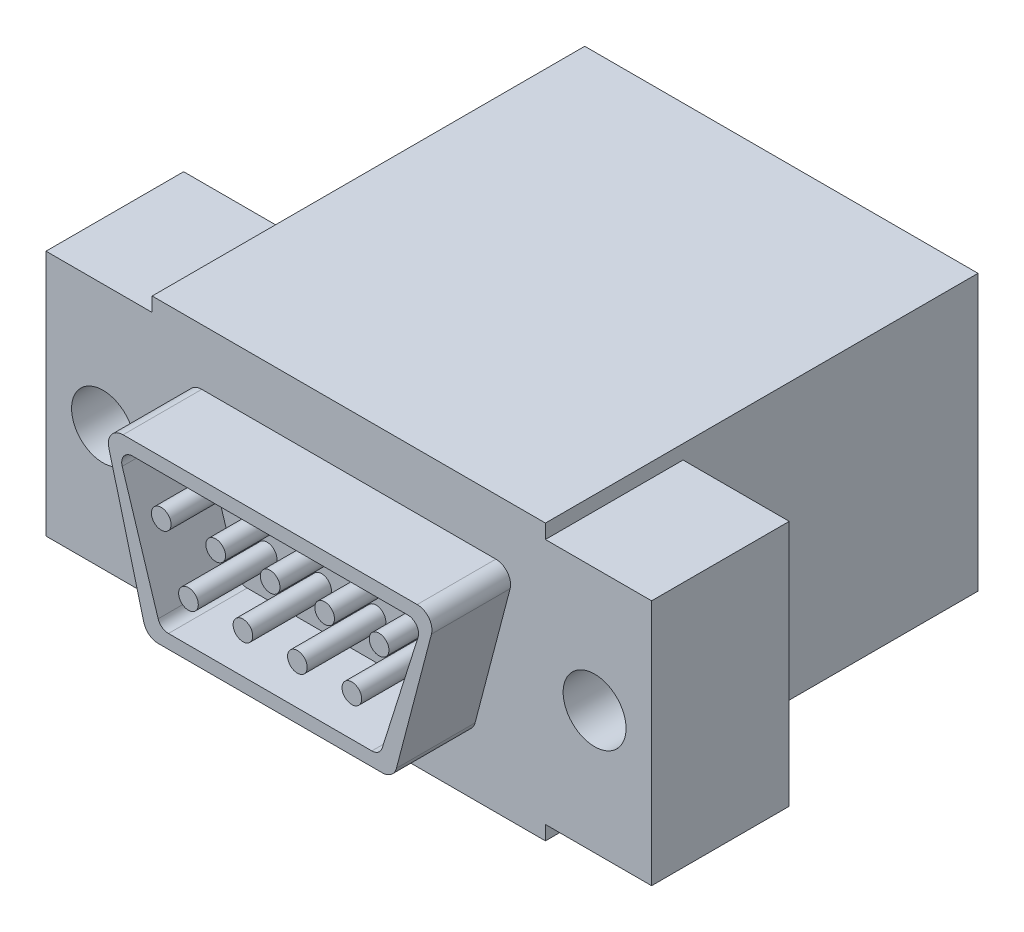
SolidWorks part; units mm, degrees
ref_plane "前视基准面" through (0, 0, 0) normal (0, 0, 1) x (1, 0, 0)
ref_plane "上视基准面" through (0, 0, 0) normal (0, 1, 0) x (1, 0, 0)
ref_plane "右视基准面" through (0, 0, 0) normal (1, 0, 0) x (0, 0, -1)
other "Configuration Table"
sketch "草图1" plane through (0, 0, 0) normal (0, 0, 1) x (1, 0, 0)
  line L1 (-15.4, -6.275) -> (15.4, -6.275)
  line L2 (-15.4, -6.275) -> (-15.4, 6.275)
  line L3 (-15.4, 6.275) -> (15.4, 6.275)
  line L4 (15.4, -6.275) -> (15.4, 6.275)
  line L5 (-15.4, -6.275) -> (15.4, 6.275) construction
  line L6 (-15.4, 6.275) -> (15.4, -6.275) construction
extrude "M3_01_ThinFlange_30.80x12.55x0.60" add sketch "草图1" against normal blind 0.6
sketch "草图2" plane through (0, 0, 0) normal (0, 0, 1) x (1, 0, 0)
  line L1 (-15.4, -6.275) -> (15.4, -6.275)
  line L2 (-15.4, -6.275) -> (-15.4, 6.275)
  line L3 (-15.4, 6.275) -> (15.4, 6.275)
  line L4 (15.4, -6.275) -> (15.4, 6.275)
  line L5 (-15.4, -6.275) -> (15.4, 6.275) construction
  line L6 (-15.4, 6.275) -> (15.4, -6.275) construction
  point P0 (0, 0)
extrude "M3_02_FirstShoulder_30.80x12.55_D7.00" add sketch "草图2" against normal blind 7
sketch "草图3" plane through (0, 0, 0) normal (0, 0, 1) x (1, 0, 0)
  line L1 (-10, -7) -> (10, -7)
  line L2 (-10, -7) -> (-10, 7)
  line L3 (-10, 7) -> (10, 7)
  line L4 (10, -7) -> (10, 7)
  line L5 (-10, -7) -> (10, 7) construction
  line L6 (-10, 7) -> (10, -7) construction
extrude "M3_03_SecondStageCore_20.00x14.00_D22.00_FromFlange" add sketch "草图3" against normal blind 22
sketch "草图4" plane through (0, 0, 0) normal (0, 0, 1) x (1, 0, 0)
  circle A0 centre (-12.5, 0) radius 2.5
  circle A1 centre (12.5, 0) radius 2.5
extrude "M3_04_SimplifiedFixedPosts_Dia5.00_L3.50" add sketch "草图4" against normal blind 3.5
sketch "草图5" plane through (0, 0, 0) normal (0, 0, 1) x (1, 0, 0)
  line L0 (-7.4781, 4.15) -> (7.4781, 4.15)
  line L1 (8.2036, 3.2099) -> (6.4217, -3.5901)
  line L2 (5.6962, -4.15) -> (-5.6962, -4.15)
  line L3 (-6.4217, -3.5901) -> (-8.2036, 3.2099)
  arc A0 (-8.2036, 3.2099) -> (-7.4781, 4.15) centre (-7.4781, 3.4) cw
  arc A1 (7.4781, 4.15) -> (8.2036, 3.2099) centre (7.4781, 3.4) cw
  arc A2 (6.4217, -3.5901) -> (5.6962, -4.15) centre (5.6962, -3.4) cw
  arc A3 (-5.6962, -4.15) -> (-6.4217, -3.5901) centre (-5.6962, -3.4) cw
extrude "M3_05_RoundedDGuide_OuterBoss_L4.00" add sketch "草图5" along normal blind 4
sketch "草图6" plane through (0, 0, 0) normal (0, 0, 1) x (1, 0, 0)
  line L0 (-7, 3.45) -> (7, 3.45)
  line L1 (7.5245, 2.7347) -> (5.6962, -3.0653)
  line L2 (5.1717, -3.45) -> (-5.1717, -3.45)
  line L3 (-5.6962, -3.0653) -> (-7.5245, 2.7347)
  arc A0 (-7.5245, 2.7347) -> (-7, 3.45) centre (-7, 2.9) cw
  arc A1 (7, 3.45) -> (7.5245, 2.7347) centre (7, 2.9) cw
  arc A2 (5.6962, -3.0653) -> (5.1717, -3.45) centre (5.1717, -2.9) cw
  arc A3 (-5.1717, -3.45) -> (-5.6962, -3.0653) centre (-5.1717, -2.9) cw
extrude "M3_06_RoundedDGuide_InnerOpening" cut sketch "草图6" along normal blind 4
sketch "草图7" plane through (0, 0, 0) normal (0, 0, 1) x (1, 0, 0)
  circle A0 centre (-5.54, 1.42) radius 0.5
  circle A1 centre (-2.77, 1.42) radius 0.5
  circle A2 centre (0, 1.42) radius 0.5
  circle A3 centre (2.77, 1.42) radius 0.5
  circle A4 centre (5.54, 1.42) radius 0.5
  circle A5 centre (-4.155, -1.42) radius 0.5
  circle A6 centre (-1.385, -1.42) radius 0.5
  circle A7 centre (1.385, -1.42) radius 0.5
  circle A8 centre (4.155, -1.42) radius 0.5
extrude "M3_07_9Pins_Dia1.00_L4.00" add sketch "草图7" along normal blind 4
sketch "草图8" plane through (0, 0, 0) normal (0, 0, 1) x (1, 0, 0)
  circle A0 centre (-12.5, 0) radius 1.6
  circle A1 centre (12.5, 0) radius 1.6
extrude "M3_08_FixedPostBores_Dia3.20_Pitch25.00" cut sketch "草图8" against normal blind 4
